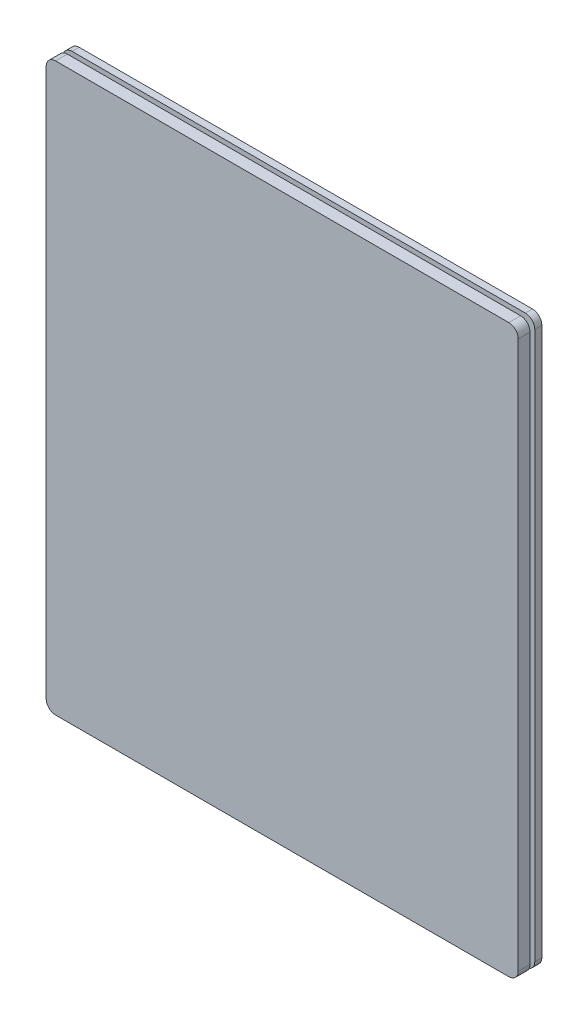
SolidWorks part; units mm, degrees
material "硅"
ref_plane "前视基准面" through (0, 0, 0) normal (0, 0, 1) x (1, 0, 0)
ref_plane "上视基准面" through (0, 0, 0) normal (0, 1, 0) x (1, 0, 0)
ref_plane "右视基准面" through (0, 0, 0) normal (1, 0, 0) x (0, 0, -1)
sketch "草图1" plane through (0, 0, 0) normal (0, 0, 1) x (1, 0, 0)
  line L1 (-5.0813, 6.8038) -> (4.9187, 6.8038)
  line L2 (-5.0813, 6.8038) -> (-5.0813, -5.1962)
  line L3 (-5.0813, -5.1962) -> (4.9187, -5.1962)
  line L4 (4.9187, 6.8038) -> (4.9187, -5.1962)
  dimension "D1" = 10
  dimension "D2" = 12
extrude "凸台-拉伸1" add sketch "草图1" along normal blind 0.6
sketch "草图2" plane through (0, 0, 0) normal (0, 0, -1) x (-1, 0, 0)
  line L1 (-2.7126, 5.7889) -> (2.884, 5.7889)
  line L2 (-3.7126, 4.7889) -> (-3.7126, -3.1159)
  line L3 (-2.7126, -4.1159) -> (2.884, -4.1159)
  line L4 (3.884, 4.7889) -> (3.884, -3.1159)
  line L5 (-4.9187, 6.8038) -> (5.0813, 6.8038)
  line L6 (-4.9187, 6.8038) -> (-4.9187, -5.1962)
  line L7 (-4.9187, -5.1962) -> (5.0813, -5.1962)
  line L8 (5.0813, 6.8038) -> (5.0813, -5.1962)
  arc A0 (3.884, 4.7889) -> (2.884, 5.7889) centre (2.884, 4.7889) ccw
  arc A1 (2.884, -4.1159) -> (3.884, -3.1159) centre (2.884, -3.1159) ccw
  arc A2 (-2.7126, -4.1159) -> (-3.7126, -3.1159) centre (-2.7126, -3.1159) cw
  arc A3 (-2.7126, 5.7889) -> (-3.7126, 4.7889) centre (-2.7126, 4.7889) ccw
  dimension "D1" = 1
extrude "切除-拉伸1" cut sketch "草图2" against normal blind 0.1
ref_plane "基准面1" through (0, 0, 0.3) normal (0, 0, 1) x (1, 0, 0)
sketch "草图4" plane through (0, 0, 0.3) normal (0, 0, 1) x (1, 0, 0)
  line L0 (0, 1.8776) -> (-0.9093, 0.8038)
  line L1 (-5.0813, 6.8038) -> (4.9187, 6.8038)
  line L2 (-5.0813, 6.8038) -> (-5.0813, -5.1962)
  line L3 (-5.0813, -5.1962) -> (4.9187, -5.1962)
  line L4 (4.9187, 6.8038) -> (4.9187, -5.1962)
  line L5 (-0.9093, 0.8038) -> (0, -0.3744)
  line L6 (0, -0.3744) -> (0.9978, 0.8038)
  line L7 (0.9978, 0.8038) -> (0, 1.8776)
extrude "切除-拉伸3" cut sketch "草图4" against normal mid plane 0.1
fillet "圆角1" radius 0.2 8 edges at (-5.0813, -5.1962, 0.175) (-5.0813, -5.1962, 0.475) (4.9187, -5.1962, 0.175) (4.9187, -5.1962, 0.475) (4.9187, 6.8038, 0.475) (4.9187, 6.8038, 0.175) (-5.0813, 6.8038, 0.475) (-5.0813, 6.8038, 0.175)
